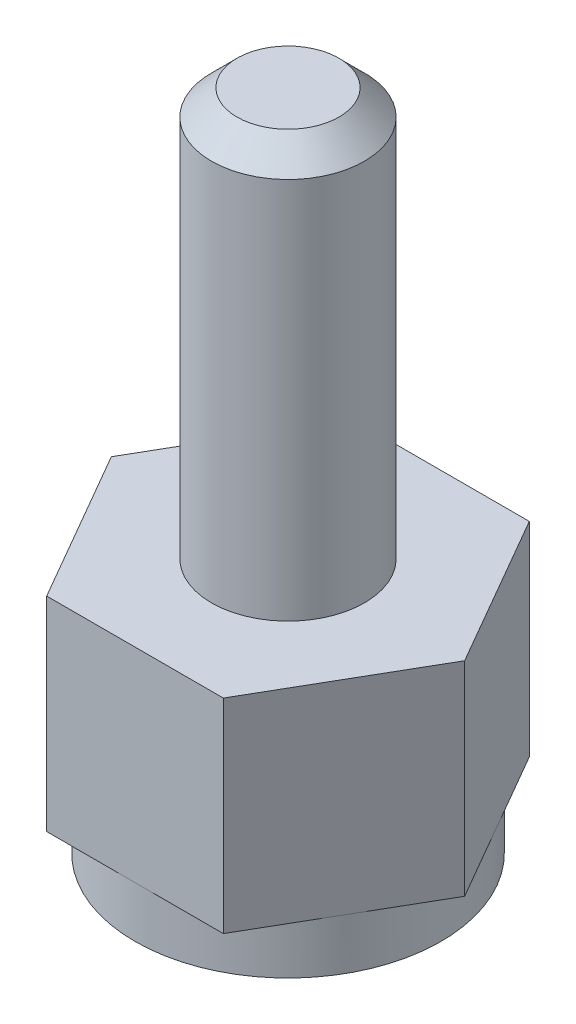
SolidWorks part; units mm, degrees
material "Nylon 101"
ref_plane "Front Plane" through (0, 0, 0) normal (0, 0, 1) x (1, 0, 0)
ref_plane "Top Plane" through (0, 0, 0) normal (0, 1, 0) x (1, 0, 0)
ref_plane "Right Plane" through (0, 0, 0) normal (1, 0, 0) x (0, 0, -1)
sketch "Sketch1" plane through (0, 0, 0) normal (0, 1, 0) x (1, 0, 0)
  circle A0 centre (0, 0) radius 3
  dimension "D1" = 6
extrude "Boss-Extrude1" add sketch "Sketch1" along normal blind 1
sketch "Sketch2" plane through (0, 1, 0) normal (0, 1, 0) x (1, 0, 0)
  line L1 (3.4641, 0) -> (1.7321, 3)
  line L2 (1.7321, 3) -> (-1.7321, 3)
  line L3 (-1.7321, 3) -> (-3.4641, 0)
  line L4 (-3.4641, 0) -> (-1.7321, -3)
  line L5 (-1.7321, -3) -> (1.7321, -3)
  line L6 (1.7321, -3) -> (3.4641, 0)
  circle A0 centre (0, 0) radius 3 construction
  circle A1 centre (0, 0) radius 3 construction
extrude "Boss-Extrude2" add sketch "Sketch2" along normal blind 4
sketch "Sketch3" plane through (0, 5, 0) normal (0, 1, 0) x (1, 0, 0)
  circle A0 centre (0, 0) radius 1.5
  dimension "D1" = 3
extrude "Boss-Extrude3" add sketch "Sketch3" along normal blind 8
chamfer "Chamfer1" distance 0.5 angle 45 1 edges at (0, 13, 1.5)
sketch "Sketch4" plane through (0, 0, 0) normal (0, -1, 0) x (1, 0, 0)
  circle A0 centre (0, 0) radius 1.5
  dimension "D1" = 3
extrude "Cut-Extrude1" cut sketch "Sketch4" against normal blind 3
